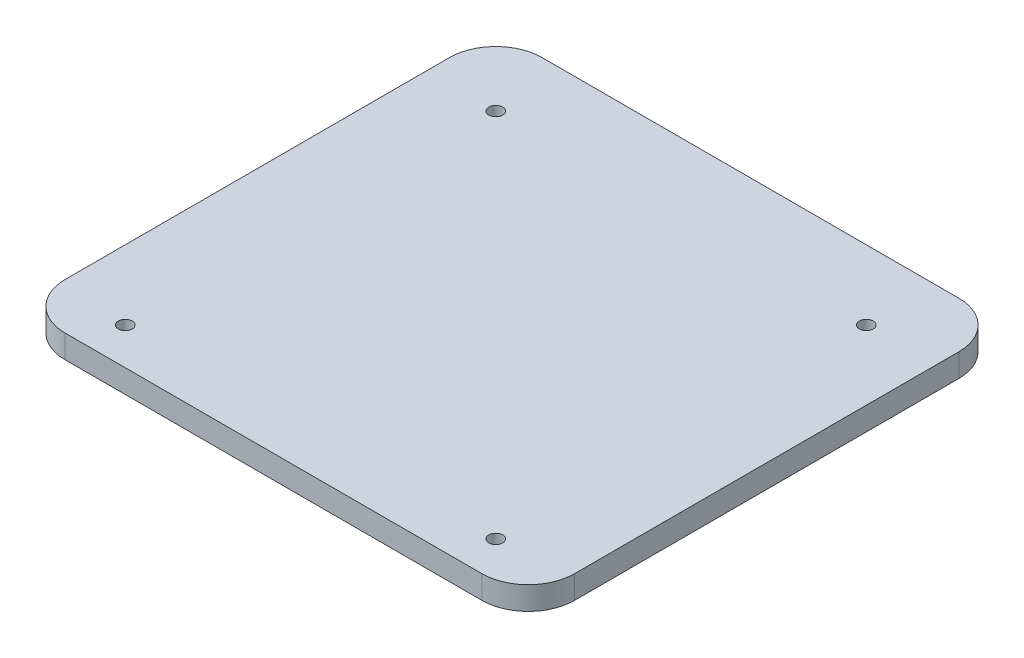
SolidWorks part; units mm, degrees
ref_plane "Front Plane" through (0, 0, 0) normal (0, 0, 1) x (1, 0, 0)
ref_plane "Top Plane" through (0, 0, 0) normal (0, 1, 0) x (1, 0, 0)
ref_plane "Right Plane" through (0, 0, 0) normal (1, 0, 0) x (0, 0, -1)
sketch "Sketch2" plane through (0, 0, 0) normal (0, 1, 0) x (1, 0, 0)
  line L0 (-55, -43.5) -> (-40, -43.5) construction
  line L1 (-55, 51.5) -> (55, 51.5)
  line L2 (-55, 51.5) -> (-55, -51.5)
  line L3 (-55, -51.5) -> (55, -51.5)
  line L4 (55, 51.5) -> (55, -51.5)
  line L5 (-55, 51.5) -> (55, -51.5) construction
  line L6 (-55, -51.5) -> (55, 51.5) construction
  line L7 (-40, -43.5) -> (-40, 36.5) construction
  line L8 (40, -43.5) -> (40, 36.5) construction
  circle A0 centre (-40, -43.5) radius 1.5
  circle A1 centre (-40, 36.5) radius 1.5
  circle A2 centre (40, -43.5) radius 1.5
  circle A3 centre (40, 36.5) radius 1.5
  point P0 (0, 0)
  dimension "D5" = 3
  dimension "D7" = 3
  dimension "D8" = 15
  dimension "D9" = 8
  dimension "D10" = 3
  dimension "D12" = 3
  dimension "D1" = 110
  dimension "D2" = 103
  dimension "D3" = 15
  dimension "D4" = 8
  dimension "D6" = 80
  dimension "D11" = 80
  dimension "D13" = 15
extrude "Boss-Extrude1" add sketch "Sketch2" along normal blind 5
fillet "Fillet1" radius 10 4 edges at (-55, 2.5, -51.5) (55, 2.5, -51.5) (55, 2.5, 51.5) (-55, 2.5, 51.5)
